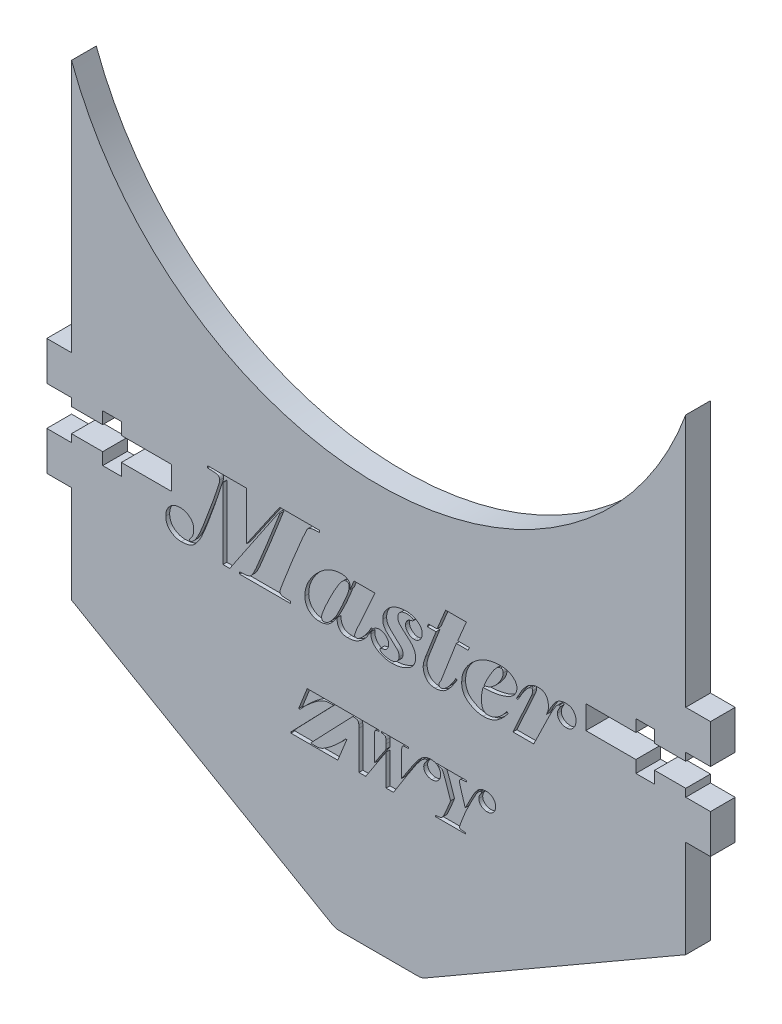
SolidWorks part; units mm, degrees
ref_plane "前视基准面" through (0, 0, 0) normal (0, 0, 1) x (1, 0, 0)
ref_plane "上视基准面" through (0, 0, 0) normal (0, 1, 0) x (1, 0, 0)
ref_plane "右视基准面" through (0, 0, 0) normal (1, 0, 0) x (0, 0, -1)
sketch "Sketch1" plane through (0, 0, 0) normal (0, 0, 1) x (1, 0, 0)
  line L0 (0, -85.8717) -> (0, 49.7374) construction
  line L2 (39.415, -20) -> (39.415, 40)
  line L4 (-39.415, -20) -> (-39.415, 40)
  line L6 (-6, -39.2922) -> (-39.415, -20)
  line L8 (6, -39.2922) -> (39.415, -20)
  line L9 (-39.415, 40) -> (39.415, 40) construction
  line L10 (5, -39.5601) -> (-5, -39.5601)
  arc A0 (39.415, 40) -> (-39.415, 40) centre (0, 54.5072) cw
  arc A3 (-6, -39.2922) -> (-5, -39.5601) centre (-5, -37.5601) ccw
  arc A4 (6, -39.2922) -> (5, -39.5601) centre (5, -37.5601) cw
  point P17 (0, -39.5601)
  dimension "D2" = 10
  dimension "D6" = 42
  dimension "D7" = 2
  dimension "D1" = 78.83
  dimension "D3" = 120
  dimension "D4" = 60
  dimension "D5" = 20
extrude "Boss-Extrude1" add sketch "Sketch1" along normal blind 3.175
sketch "Sketch2" plane through (0, 0, 3.175) normal (0, 0, 1) x (1, 0, 0)
  line L0 (-41.5791, 0) -> (41.497, 0) construction
  line L1 (0, 0) -> (0, 24.816) construction
  line L2 (39.415, -2.5) -> (39.415, -7.5)
  line L3 (39.415, -20) -> (39.415, 40) construction
  line L4 (39.415, -7.5) -> (42.59, -7.5)
  line L5 (42.59, -7.5) -> (42.59, -2.5)
  line L6 (42.59, -2.5) -> (39.415, -2.5)
  line L7 (39.415, -5) -> (51.6041, -5) construction
  line L8 (42.59, 2.5) -> (39.415, 2.5)
  line L9 (42.59, 7.5) -> (42.59, 2.5)
  line L10 (39.415, 7.5) -> (42.59, 7.5)
  line L11 (39.415, 2.5) -> (39.415, 7.5)
  line L12 (-39.415, -5) -> (-51.6041, -5) construction
  line L13 (-39.415, 2.5) -> (-39.415, 7.5)
  line L14 (-39.415, 7.5) -> (-42.59, 7.5)
  line L15 (-42.59, 7.5) -> (-42.59, 2.5)
  line L16 (-42.59, 2.5) -> (-39.415, 2.5)
  line L17 (-42.59, -2.5) -> (-39.415, -2.5)
  line L18 (-42.59, -7.5) -> (-42.59, -2.5)
  line L19 (-39.415, -7.5) -> (-42.59, -7.5)
  line L20 (-39.415, -2.5) -> (-39.415, -7.5)
  dimension "D1" = 5
  dimension "D2" = 3.175
  dimension "D3" = 5
extrude "Boss-Extrude2" add sketch "Sketch2" against normal blind 3.175
sketch "Sketch3" plane through (0, 0, 3.175) normal (0, 0, 1) x (1, 0, 0)
  line L0 (-43.1526, 0) -> (45.3724, 0) construction
  line L1 (39.415, 1.5) -> (35.415, 1.5)
  line L2 (39.415, 7.5) -> (39.415, 40) construction
  line L3 (35.415, 1.5) -> (35.415, 3.05)
  line L4 (35.415, 3.05) -> (33.015, 3.05)
  line L5 (33.015, 3.05) -> (33.015, 1.5)
  line L6 (33.015, 1.5) -> (26.59, 1.5)
  line L7 (39.415, 1.5) -> (39.415, -1.5)
  line L8 (26.59, 1.5) -> (26.59, -1.5)
  line L9 (33.015, -1.5) -> (26.59, -1.5)
  line L10 (33.015, -3.05) -> (33.015, -1.5)
  line L11 (35.415, -3.05) -> (33.015, -3.05)
  line L12 (35.415, -1.5) -> (35.415, -3.05)
  line L13 (39.415, -1.5) -> (35.415, -1.5)
  line L14 (42.59, -7.5) -> (42.59, -2.5) construction
  line L15 (0, 0) -> (0, 9.8166) construction
  line L16 (-39.415, -1.5) -> (-35.415, -1.5)
  line L17 (-35.415, -1.5) -> (-35.415, -3.05)
  line L18 (-35.415, -3.05) -> (-33.015, -3.05)
  line L19 (-33.015, -3.05) -> (-33.015, -1.5)
  line L20 (-33.015, -1.5) -> (-26.59, -1.5)
  line L21 (-26.59, 1.5) -> (-26.59, -1.5)
  line L22 (-39.415, 1.5) -> (-39.415, -1.5)
  line L23 (-33.015, 1.5) -> (-26.59, 1.5)
  line L24 (-33.015, 3.05) -> (-33.015, 1.5)
  line L25 (-35.415, 3.05) -> (-33.015, 3.05)
  line L26 (-35.415, 1.5) -> (-35.415, 3.05)
  line L27 (-39.415, 1.5) -> (-35.415, 1.5)
  point P14 (26.59, 0)
  point P15 (39.415, 0)
  point P35 (-39.415, 0)
  point P36 (-26.59, 0)
  dimension "D1" = 6.1
  dimension "D2" = 3
  dimension "D3" = 2.4
  dimension "D4" = 16
  dimension "D5" = 4
extrude "Cut-Extrude1" cut sketch "Sketch3" against normal through all
sketch "Sketch4" plane through (0, 0, 3.175) normal (0, 0, 1) x (1, 0, 0)
  line L0 (-26.9387, -6.3269) -> (30.0115, -6.3269) construction
  line L1 (-11.035, -20.7085) -> (16.6466, -20.7085) construction
  text T0 "Master" font "Elephant" height 10
  text T1 "ZWY" font "Elephant" height 6
extrude "Cut-Extrude2" cut sketch "Sketch4" against normal blind 0.5
